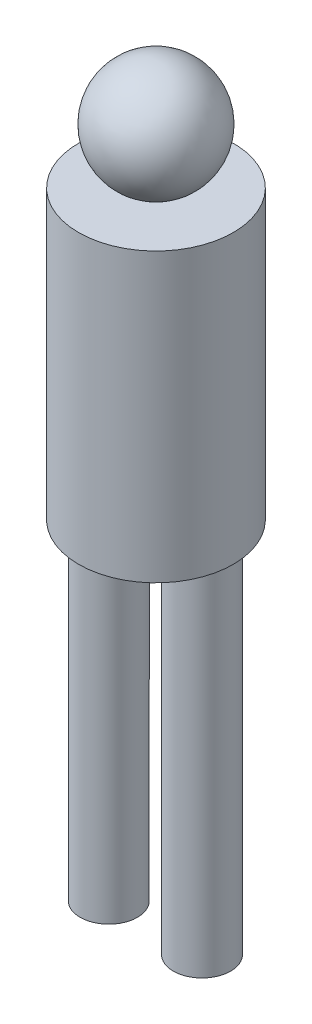
SolidWorks part; units mm, degrees
ref_plane "Front Plane" through (0, 0, 0) normal (0, 0, 1) x (1, 0, 0)
ref_plane "Top Plane" through (0, 0, 0) normal (0, 1, 0) x (1, 0, 0)
ref_plane "Right Plane" through (0, 0, 0) normal (1, 0, 0) x (0, 0, -1)
sketch "Sketch1" plane through (0, 0, 0) normal (0, 1, 0) x (1, 0, 0)
  circle A0 centre (0, 0) radius 177.8
  dimension "D1" = 355.6
extrude "Boss-Extrude1" add sketch "Sketch1" along normal blind 660.4
sketch "Sketch2" plane through (0, 0, 0) normal (1, 0, 0) x (0, 0, -1)
  line L0 (0, 660.4) -> (0, 914.4) construction
  line L1 (177.8, 660.4) -> (-177.8, 660.4) construction
  line L2 (0, 914.4) -> (0, 660.4)
  arc A0 (0, 914.4) -> (0, 660.4) centre (0, 787.4) cw
  dimension "D1" = 254
revolve "Revolve1" add sketch "Sketch2" angle 360 about L0
sketch "Sketch3" plane through (0, 0, 0) normal (0, -1, 0) x (-1, 0, 0)
  circle A0 centre (108.3847, 0) radius 65.8136
  circle A1 centre (-105.8353, 0) radius 65.8136
extrude "Boss-Extrude2" add sketch "Sketch3" along normal blind 812.8
sketch "Sketch4" plane through (0, 0, 0) normal (0, 0, 1) x (1, 0, 0)
  line L1 (-174.1983, -812.8) -> (171.6489, -812.8) construction
  line L2 (-174.1983, -812.8) -> (-174.1983, 1017.0426) construction
  line L3 (-174.1983, 1017.0426) -> (171.6489, 1017.0426) construction
  line L4 (171.6489, -812.8) -> (171.6489, 1017.0426) construction
  dimension "D1" = 1829.8426
